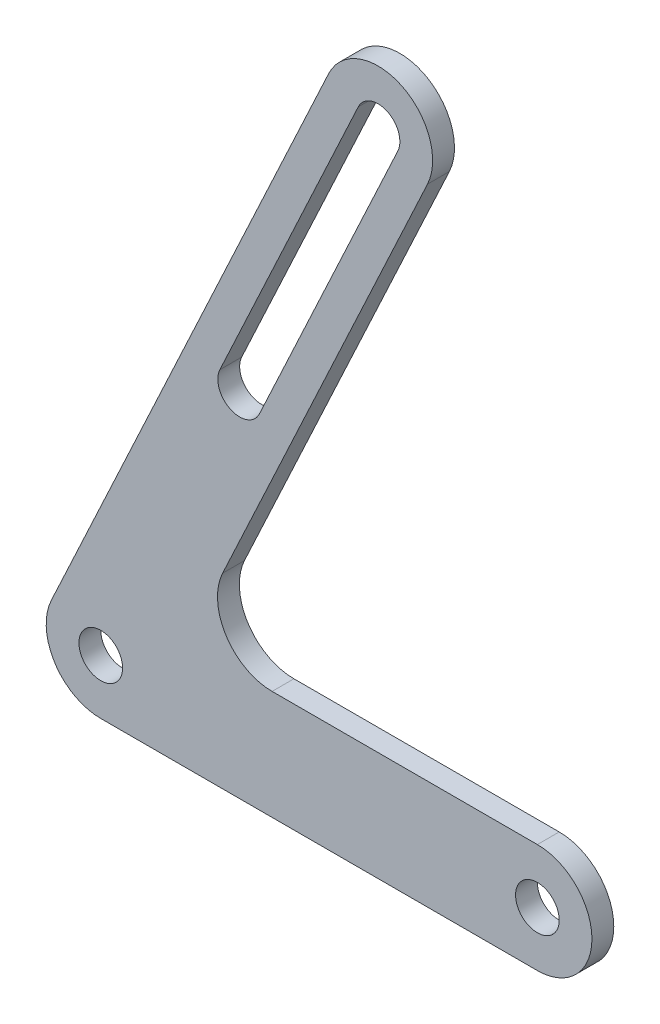
SolidWorks part; units mm, degrees
ref_plane "Front Plane" through (0, 0, 0) normal (0, 0, 1) x (1, 0, 0)
ref_plane "Top Plane" through (0, 0, 0) normal (0, 1, 0) x (1, 0, 0)
ref_plane "Right Plane" through (0, 0, 0) normal (1, 0, 0) x (0, 0, -1)
sketch "Sketch2" plane through (0, 0, 0) normal (0, 0, 1) x (1, 0, 0)
  line L0 (0, 0) -> (80, 0) construction
  line L1 (80, 0) -> (50.8059, 108.9537) construction
  line L2 (50.8059, 108.9537) -> (0, 0) construction
  line L3 (0, 0) -> (50.8059, 108.9537) construction
  line L4 (-9.0631, 4.2262) -> (41.7429, 113.1799)
  line L5 (9.0631, -4.2262) -> (59.869, 104.7275)
  line L6 (0, 0) -> (80, 0) construction
  line L7 (0, 10) -> (80, 10)
  line L8 (0, -10) -> (80, -10)
  arc A0 (-9.0631, 4.2262) -> (9.0631, -4.2262) centre (0, 0) ccw
  arc A1 (59.869, 104.7275) -> (41.7429, 113.1799) centre (50.8059, 108.9537) ccw
  arc A2 (0, 10) -> (0, -10) centre (0, 0) ccw
  arc A3 (80, -10) -> (80, 10) centre (80, 0) ccw
  point P3 (25.403, 54.4768)
  point P10 (40, 0)
  dimension "D4" = 10
  dimension "D5" = 10
  dimension "D1" = 75
  dimension "D2" = 65
  dimension "D3" = 80
extrude "Boss-Extrude1" add sketch "Sketch2" along normal mid plane 4 contours L7 A2 A0 L5 | A2 L7 L5 A1 L4 | L8 A3 L7 L5 A0
sketch "Sketch3" plane through (0, 0, 0) normal (0, 0, 1) x (1, 0, 0)
  line L0 (50.8059, 108.9537) -> (25.4488, 54.5752) construction
  line L1 (54.4312, 107.2632) -> (29.0741, 52.8848)
  line L2 (47.1807, 110.6442) -> (21.8236, 56.2657)
  line L3 (-9.0631, 4.2262) -> (41.7429, 113.1799) construction
  line L4 (80, 10) -> (15.6969, 10)
  line L5 (15.6969, 10) -> (59.869, 104.7275)
  line L6 (41.7429, 113.1799) -> (-9.0631, 4.2262)
  line L7 (0, -10) -> (80, -10)
  line L8 (80, 10) -> (15.6969, 10)
  line L9 (15.6969, 10) -> (59.869, 104.7275)
  line L10 (41.7429, 113.1799) -> (-9.0631, 4.2262)
  line L11 (0, -10) -> (80, -10)
  arc A0 (54.4312, 107.2632) -> (47.1807, 110.6442) centre (50.8059, 108.9537) ccw
  arc A1 (21.8236, 56.2657) -> (29.0741, 52.8848) centre (25.4488, 54.5752) ccw
  arc A3 (59.869, 104.7275) -> (41.7429, 113.1799) centre (50.8059, 108.9537) ccw
  arc A4 (-9.0631, 4.2262) -> (0, -10) centre (0, 0) ccw
  arc A5 (80, -10) -> (80, 10) centre (80, 0) ccw
  arc A6 (59.869, 104.7275) -> (41.7429, 113.1799) centre (50.8059, 108.9537) ccw
  arc A7 (-9.0631, 4.2262) -> (0, -10) centre (0, 0) ccw
  arc A8 (80, -10) -> (80, 10) centre (80, 0) ccw
  point P9 (38.1274, 81.7645)
  dimension "D2" = 4
  dimension "D3" = 60
  dimension "D1" = 0
extrude "Cut-Extrude1" cut sketch "Sketch3" against normal through all both and the other way through all contours L2 A1 L1 A0
sketch "Sketch4" plane through (0, 0, 0) normal (0, 0, 1) x (1, 0, 0)
  line L4 (80, 10) -> (15.6969, 10)
  line L5 (15.6969, 10) -> (59.869, 104.7275)
  line L6 (41.7429, 113.1799) -> (-9.0631, 4.2262)
  line L7 (0, -10) -> (80, -10)
  line L8 (80, 10) -> (15.6969, 10)
  line L9 (15.6969, 10) -> (59.869, 104.7275)
  line L10 (41.7429, 113.1799) -> (-9.0631, 4.2262)
  line L11 (0, -10) -> (80, -10)
  circle A0 centre (80, 0) radius 4
  circle A1 centre (0, 0) radius 4
  arc A3 (59.869, 104.7275) -> (41.7429, 113.1799) centre (50.8059, 108.9537) ccw
  arc A4 (-9.0631, 4.2262) -> (0, -10) centre (0, 0) ccw
  arc A5 (80, -10) -> (80, 10) centre (80, 0) ccw
  arc A6 (59.869, 104.7275) -> (41.7429, 113.1799) centre (50.8059, 108.9537) ccw
  arc A7 (-9.0631, 4.2262) -> (0, -10) centre (0, 0) ccw
  arc A8 (80, -10) -> (80, 10) centre (80, 0) ccw
  dimension "D2" = 8
  dimension "D1" = 0
extrude "Cut-Extrude2" cut sketch "Sketch4" against normal through all both and the other way through all contours A1 | A0
fillet "Fillet2" radius 10 1 edges at (15.6969, 10, 0)
